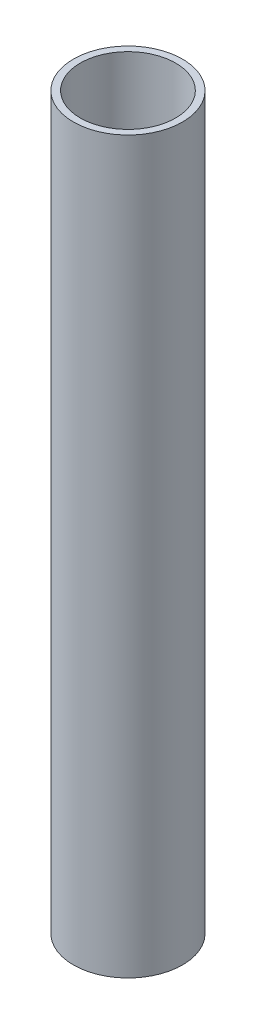
SolidWorks part; units mm, degrees
material "Glass"
ref_plane "Front Plane" through (0, 0, 0) normal (0, 0, 1) x (1, 0, 0)
ref_plane "Top Plane" through (0, 0, 0) normal (0, 1, 0) x (1, 0, 0)
ref_plane "Right Plane" through (0, 0, 0) normal (1, 0, 0) x (0, 0, -1)
sketch "Sketch1" plane through (0, 0, 0) normal (0, 0, 1) x (1, 0, 0)
  line L0 (0, 0) -> (6.35, 0)
  line L1 (0, 1) -> (5.55, 1)
  line L2 (6.35, 0) -> (6.35, 85)
  line L3 (5.55, 1) -> (5.55, 85)
  line L4 (5.55, 85) -> (6.35, 85)
  line L5 (0, 1) -> (0, 0) construction
  line L6 (0, 0) -> (0, 1)
  dimension "D1" = 6.35
  dimension "D2" = 1
  dimension "D3" = 0.8
  dimension "D4" = 85
revolve "Test Tube" add sketch "Sketch1" angle 360 about L5
sketch "5 mL Line" plane through (0, 0, 0) normal (0, 0, 1) x (1, 0, 0)
  line L0 (-16.0953, 48) -> (20.7544, 48)
  line L1 (-6.35, 0) -> (6.35, 0) construction
  line L2 (-16.0953, 56.9) -> (20.7544, 56.9)
  dimension "D1" = 48
  dimension "D2" = 8.9
